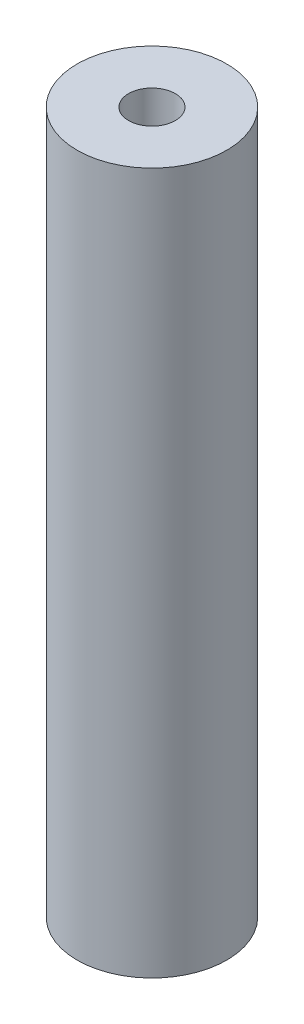
SolidWorks part; units mm, degrees
material "普通碳钢"
ref_plane "前视基准面" through (0, 0, 0) normal (0, 0, 1) x (1, 0, 0)
ref_plane "上视基准面" through (0, 0, 0) normal (0, 1, 0) x (1, 0, 0)
ref_plane "右视基准面" through (0, 0, 0) normal (1, 0, 0) x (0, 0, -1)
sketch "草图1" plane through (0, 0, 0) normal (0, 1, 0) x (1, 0, 0)
  circle A0 centre (0, 0) radius 8
  dimension "D1" = 16
extrude "凸台-拉伸1" add sketch "草图1" along normal mid plane 75
sketch "草图2" plane through (0, 37.5, 0) normal (0, 1, 0) x (1, 0, 0)
  circle A0 centre (0, 0) radius 5
  dimension "D1" = 10
extrude "切除-拉伸1" [suppressed] cut sketch "草图2" against normal through all
hole_wizard "M6 螺纹孔1" positions "草图4" profile "草图3" tap size "M6" standard "GB"
sketch "草图4" plane through (0, 37.5, 0) normal (0, 1, 0) x (1, 0, 0)
  point P0 (0, 0)
sketch "草图3" plane through (0, 37.5, 0) normal (1, 0, 0) x (0, 0, 1)
  line L0 (0, 0) -> (0, 18.5022)
  line L1 (0, 18.5022) -> (2.5, 17)
  line L2 (2.5, 17) -> (2.5, 0)
  line L5 (2.5, 0) -> (0, 0)
  line L10 (0, 18.5022) -> (-2.5, 17) construction
  line L11 (0, -6.35) -> (0, 107.95) construction
  dimension "螺纹孔钻头直径" = 5
  dimension "螺纹孔钻头深度" = 17
  dimension "导头角度" = 118
cosmetic thread "孔螺蚊线1" parameters "D1"=12, "D2"=6
mirror "镜向1" about plane through (0, 0, 0) normal (0, 1, 0) of "M6 螺纹孔1"
